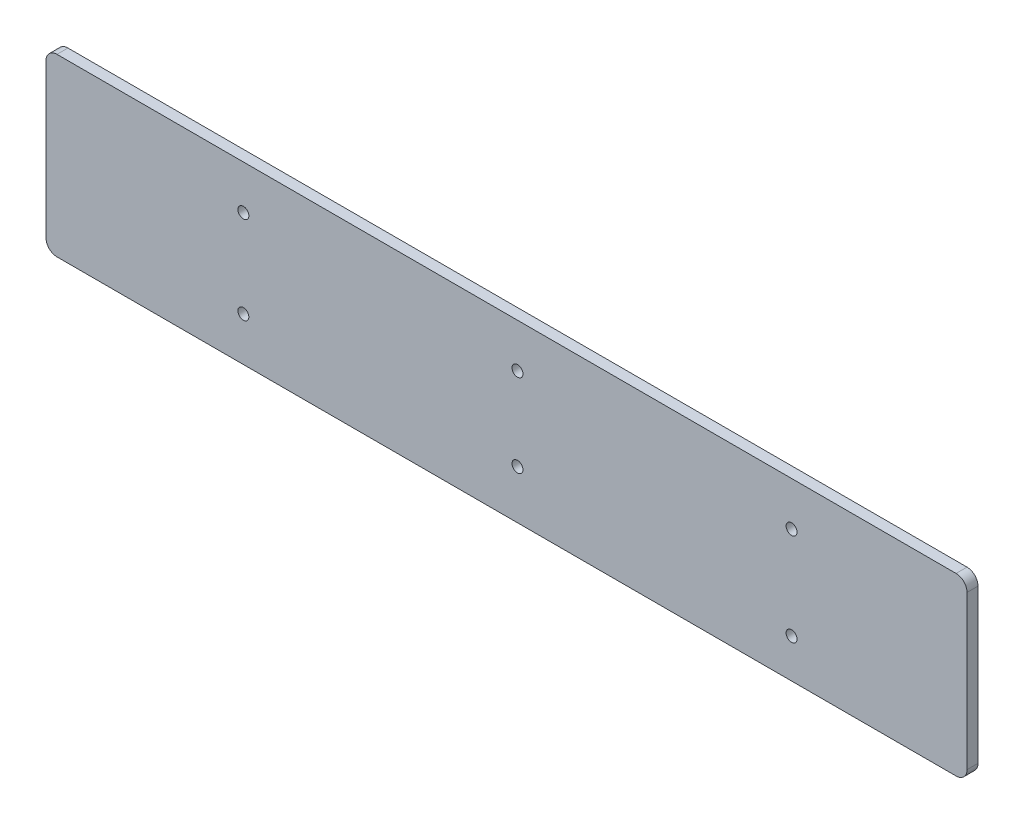
SolidWorks part; units mm, degrees
ref_plane "Front Plane" through (0, 0, 0) normal (0, 0, 1) x (1, 0, 0)
ref_plane "Top Plane" through (0, 0, 0) normal (0, 1, 0) x (1, 0, 0)
ref_plane "Right Plane" through (0, 0, 0) normal (1, 0, 0) x (0, 0, -1)
sketch "Sketch1" plane through (0, 0, 0) normal (0, 0, 1) x (1, 0, 0)
  line L1 (207.5093, -51.1442) -> (-212.4907, -51.1442)
  line L2 (207.5093, -51.1442) -> (207.5093, 28.8558)
  line L3 (207.5093, 28.8558) -> (-212.4907, 28.8558)
  line L4 (-212.4907, -51.1442) -> (-212.4907, 28.8558)
  line L5 (207.5093, -51.1442) -> (-212.4907, 28.8558) construction
  line L6 (207.5093, 28.8558) -> (-212.4907, -51.1442) construction
  circle A0 centre (-122.4907, -31.1442) radius 2.5
  circle A1 centre (-122.4907, 8.8558) radius 2.5
  circle A2 centre (2.5093, 8.8558) radius 2.5
  circle A3 centre (2.5093, -28.9788) radius 2.5
  circle A4 centre (127.5093, 8.8558) radius 2.5
  circle A5 centre (127.5093, -33.3612) radius 2.5
  point P0 (-2.4907, -11.1442)
  dimension "D3" = 5
  dimension "D4" = 5
  dimension "D6" = 60
  dimension "D8" = 5
  dimension "D9" = 5
  dimension "D10" = 125
  dimension "D11" = 5
  dimension "D12" = 5
  dimension "D13" = 125
  dimension "D1" = 420
  dimension "D2" = 80
  dimension "D5" = 90
  dimension "D7" = 20
  dimension "D14" = 80
extrude "Boss-Extrude1" add sketch "Sketch1" along normal blind 5
fillet "Fillet1" radius 5 4 edges at (-212.4907, 28.8558, 2.5) (207.5093, -51.1442, 2.5) (207.5093, 28.8558, 2.5) (-212.4907, -51.1442, 2.5)
